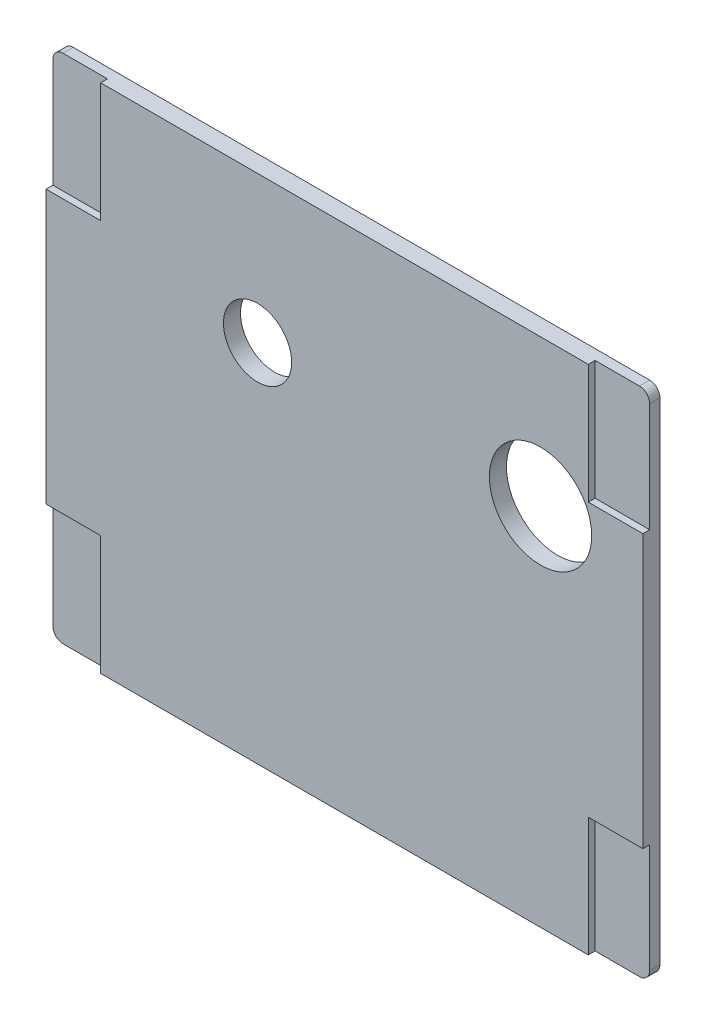
SolidWorks part; units mm, degrees
ref_plane "Front Plane" through (0, 0, 0) normal (0, 0, 1) x (1, 0, 0)
ref_plane "Top Plane" through (0, 0, 0) normal (0, 1, 0) x (1, 0, 0)
ref_plane "Right Plane" through (0, 0, 0) normal (1, 0, 0) x (0, 0, -1)
sketch "Sketch1" plane through (0, 0, 0) normal (0, 0, 1) x (1, 0, 0)
  line L1 (0, 0) -> (-175, 0)
  line L2 (0, 0) -> (0, -150)
  line L3 (0, -150) -> (-175, -150)
  line L4 (-175, 0) -> (-175, -150)
  dimension "D1" = 175
  dimension "D2" = 150
extrude "Boss-Extrude1" add sketch "Sketch1" along normal blind 5
sketch "Sketch3" plane through (0, 0, 5) normal (0, 0, 1) x (1, 0, 0)
  line L1 (0, 0) -> (-175, 0) construction
  line L2 (-175, 0) -> (-175, -150) construction
  line L3 (0, -150) -> (0, 0) construction
  circle A0 centre (-30, -43) radius 15
  circle A1 centre (-113, -43) radius 10
  dimension "D1" = 30
  dimension "D2" = 20
  dimension "D3" = 43
  dimension "D4" = 62
  dimension "D5" = 43
  dimension "D6" = 30
extrude "Cut-Extrude1" cut sketch "Sketch3" against normal up to surface (5 mm away) up to face at (-87.5, -75, 0)
sketch "Sketch4" plane through (0, 0, 5) normal (0, 0, 1) x (1, 0, 0)
  line L1 (-175, 0) -> (-159, 0)
  line L2 (-175, 0) -> (-175, -35)
  line L3 (-175, -35) -> (-159, -35)
  line L4 (-159, 0) -> (-159, -35)
  line L5 (0, 0) -> (-16, 0)
  line L6 (0, 0) -> (0, -35)
  line L7 (0, -35) -> (-16, -35)
  line L8 (-16, 0) -> (-16, -35)
  line L9 (0, -150) -> (-16, -150)
  line L10 (0, -150) -> (0, -115)
  line L11 (0, -115) -> (-16, -115)
  line L12 (-16, -150) -> (-16, -115)
  line L13 (-175, -150) -> (-159, -150)
  line L14 (-175, -150) -> (-175, -115)
  line L15 (-175, -115) -> (-159, -115)
  line L16 (-159, -150) -> (-159, -115)
  dimension "D1" = 35
  dimension "D2" = 16
extrude "Cut-Extrude2" cut sketch "Sketch4" against normal blind 2
fillet "Fillet1" radius 3 4 edges at (-175, 0, 1.5) (-175, -150, 1.5) (0, -150, 1.5) (0, 0, 1.5)
